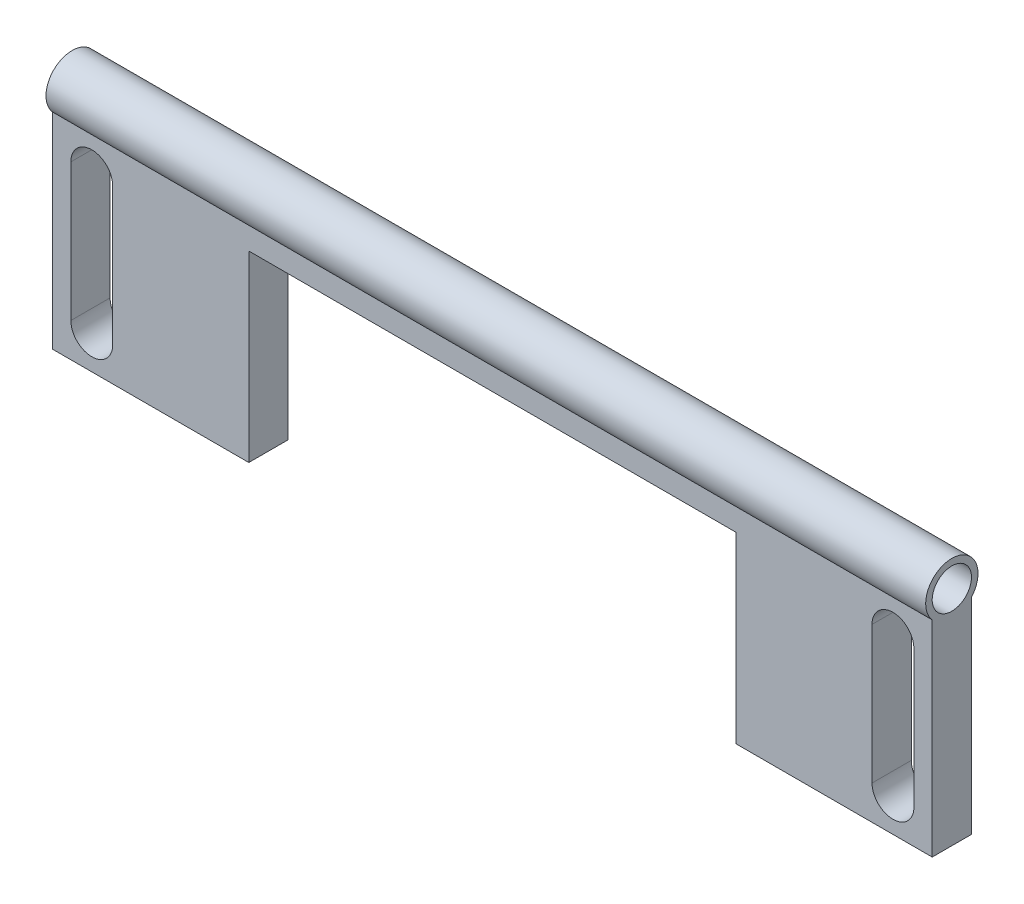
SolidWorks part; units mm, degrees
ref_plane "Front Plane" through (0, 0, 0) normal (0, 0, 1) x (1, 0, 0)
ref_plane "Top Plane" through (0, 0, 0) normal (0, 1, 0) x (1, 0, 0)
ref_plane "Right Plane" through (0, 0, 0) normal (1, 0, 0) x (0, 0, -1)
sketch "Sketch1" plane through (0, 0, 0) normal (1, 0, 0) x (0, 0, -1)
  line L0 (0, 15.7) -> (0, 0)
  line L1 (0, 0) -> (3, 0)
  line L2 (3, 0) -> (3, 15.7)
  circle A0 centre (1.5, 17.0229) radius 1.5
  arc A1 (0, 15.7) -> (3, 15.7) centre (1.5, 17.0229) cw
  dimension "D3" = 3
  dimension "D1" = 3
  dimension "D2" = 15.7
  dimension "D4" = 2
  dimension "D5" = 1.5
extrude "Boss-Extrude1" add sketch "Sketch1" along normal blind 33.615 contours A1 L0 L1 L2 A0
sketch "Sketch2" plane through (0, 0, -3) normal (0, 0, -1) x (-1, 0, 0)
  line L0 (-3, 13.1) -> (-3, 2.6) construction
  line L1 (-1.4, 13.1) -> (-1.4, 2.6)
  line L2 (-4.6, 13.1) -> (-4.6, 2.6)
  line L3 (0, 0) -> (0, 15.7) construction
  line L4 (-33.615, 0) -> (0, 0) construction
  arc A0 (-1.4, 13.1) -> (-4.6, 13.1) centre (-3, 13.1) ccw
  arc A1 (-4.6, 2.6) -> (-1.4, 2.6) centre (-3, 2.6) ccw
  point P2 (-3, 7.85)
  dimension "D1" = 1.6
  dimension "D2" = 10.5
  dimension "D3" = 3
  dimension "D4" = 7.85
extrude "Cut-Extrude1" cut sketch "Sketch2" against normal through all
mirror "Mirror1" about plane through (33.615, 0, 0) normal (1, 0, 0) of "Cut-Extrude1", "Boss-Extrude1"
sketch "Sketch3" plane through (0, 0, -3) normal (0, 0, -1) x (-1, 0, 0)
  line L0 (-52.23, 14) -> (-52.23, 0)
  line L1 (-52.23, 14) -> (-15, 14)
  line L2 (-15, 0) -> (-52.23, 0)
  line L3 (-15, 14) -> (-15, 0)
  line L4 (0, 0) -> (0, 15.7) construction
  line L5 (-67.23, 0) -> (0, 0) construction
  line L6 (-62.63, 13.1) -> (-62.63, 2.6) construction
  dimension "D1" = 10.4
  dimension "D4" = 15
extrude "Cut-Extrude3" cut sketch "Sketch3" against normal blind 10
